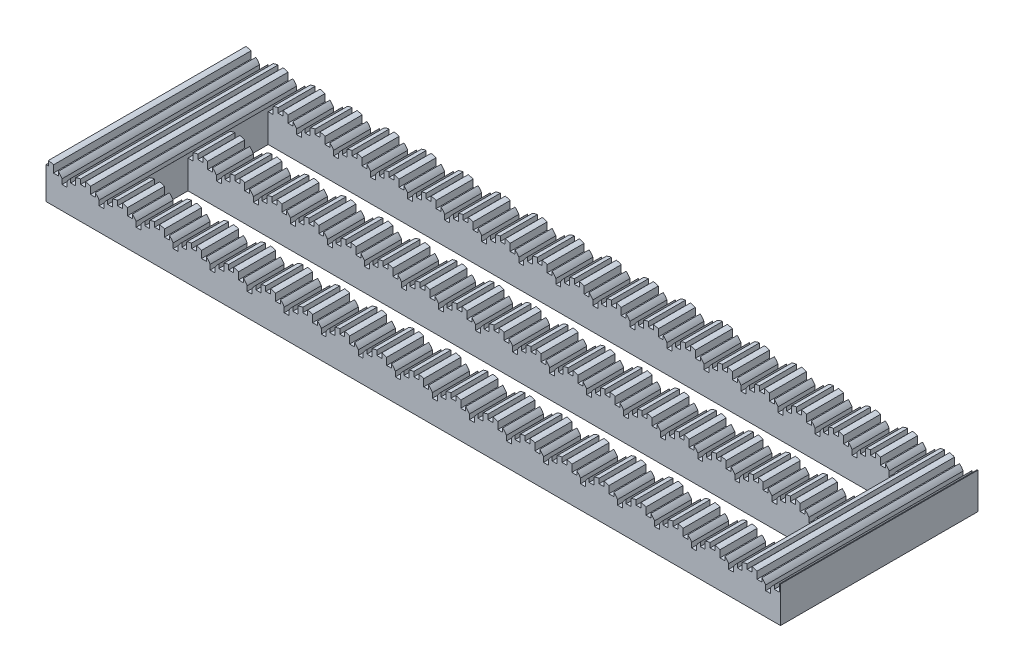
SolidWorks part; units mm, degrees
ref_plane "Front Plane" through (0, 0, 0) normal (0, 0, 1) x (1, 0, 0)
ref_plane "Top Plane" through (0, 0, 0) normal (0, 1, 0) x (1, 0, 0)
ref_plane "Right Plane" through (0, 0, 0) normal (1, 0, 0) x (0, 0, -1)
sketch "Sketch1" plane through (0, 0, 0) normal (0, 1, 0) x (1, 0, 0)
  line L1 (-59.5, -16) -> (59.5, -16)
  line L2 (-59.5, -16) -> (-59.5, 16)
  line L3 (-59.5, 16) -> (59.5, 16)
  line L4 (59.5, -16) -> (59.5, 16)
  line L5 (-59.5, -16) -> (59.5, 16) construction
  line L6 (-59.5, 16) -> (59.5, -16) construction
  line L7 (-49.5, 10) -> (53, 10)
  line L8 (-49.5, 10) -> (-49.5, 3)
  line L9 (-49.5, 3) -> (53, 3)
  line L10 (53, 10) -> (53, 3)
  line L11 (-49.5, -3) -> (53, -3)
  line L12 (-49.5, -3) -> (-49.5, -10)
  line L13 (-49.5, -10) -> (53, -10)
  line L14 (53, -3) -> (53, -10)
  point P0 (0, 0)
  dimension "D1" = 119
  dimension "D2" = 32
  dimension "D3" = 7
  dimension "D4" = 7
  dimension "D5" = 6
  dimension "D6" = 6
  dimension "D7" = 10
  dimension "D8" = 10
  dimension "D9" = 6.5
  dimension "D10" = 6.5
extrude "Boss-Extrude1" add sketch "Sketch1" along normal blind 6
sketch "Sketch2" plane through (0, 0, 16) normal (0, 0, 1) x (1, 0, 0)
  line L0 (-59.5, 6) -> (-59.5, 0) construction
  line L1 (-56.5828, 3.7) -> (-56.4172, 3.7)
  line L3 (-59.5, 6) -> (59.5, 6) construction
  line L4 (-50.5828, 3.7) -> (-50.4172, 3.7)
  line L5 (-44.5828, 3.7) -> (-44.4172, 3.7)
  line L6 (-59.5, 6) -> (-59.5, 9.8546)
  line L7 (-59.5, 9.8546) -> (59.5, 9.8546)
  line L8 (59.5, 9.8546) -> (59.5, 5.8284)
  line L9 (-38.5828, 3.7) -> (-38.4172, 3.7)
  line L10 (-32.5828, 3.7) -> (-32.4172, 3.7)
  line L11 (-26.5828, 3.7) -> (-26.4172, 3.7)
  line L12 (-20.5828, 3.7) -> (-20.4172, 3.7)
  line L13 (-14.5828, 3.7) -> (-14.4172, 3.7)
  line L14 (-8.5828, 3.7) -> (-8.4172, 3.7)
  line L15 (-2.5828, 3.7) -> (-2.4172, 3.7)
  line L16 (3.4172, 3.7) -> (3.5828, 3.7)
  line L17 (9.4172, 3.7) -> (9.5828, 3.7)
  line L18 (15.4172, 3.7) -> (15.5828, 3.7)
  line L19 (21.4172, 3.7) -> (21.5828, 3.7)
  line L20 (27.4172, 3.7) -> (27.5828, 3.7)
  line L21 (33.4172, 3.7) -> (33.5828, 3.7)
  line L22 (39.4172, 3.7) -> (39.5828, 3.7)
  line L23 (45.4172, 3.7) -> (45.5828, 3.7)
  line L24 (51.4172, 3.7) -> (51.5828, 3.7)
  line L25 (57.4172, 3.7) -> (57.5828, 3.7)
  arc A0 (-59.5, 6) -> (-56.5828, 3.7) centre (-59.5, 3) cw
  arc A1 (-50.5828, 3.7) -> (-56.4172, 3.7) centre (-53.5, 3) ccw
  arc A2 (-44.5828, 3.7) -> (-50.4172, 3.7) centre (-47.5, 3) ccw
  arc A3 (-38.5828, 3.7) -> (-44.4172, 3.7) centre (-41.5, 3) ccw
  arc A4 (-32.5828, 3.7) -> (-38.4172, 3.7) centre (-35.5, 3) ccw
  arc A5 (-26.5828, 3.7) -> (-32.4172, 3.7) centre (-29.5, 3) ccw
  arc A6 (-20.5828, 3.7) -> (-26.4172, 3.7) centre (-23.5, 3) ccw
  arc A7 (-14.5828, 3.7) -> (-20.4172, 3.7) centre (-17.5, 3) ccw
  arc A8 (-8.5828, 3.7) -> (-14.4172, 3.7) centre (-11.5, 3) ccw
  arc A9 (-2.5828, 3.7) -> (-8.4172, 3.7) centre (-5.5, 3) ccw
  arc A10 (3.4172, 3.7) -> (-2.4172, 3.7) centre (0.5, 3) ccw
  arc A11 (9.4172, 3.7) -> (3.5828, 3.7) centre (6.5, 3) ccw
  arc A12 (15.4172, 3.7) -> (9.5828, 3.7) centre (12.5, 3) ccw
  arc A13 (21.4172, 3.7) -> (15.5828, 3.7) centre (18.5, 3) ccw
  arc A14 (27.4172, 3.7) -> (21.5828, 3.7) centre (24.5, 3) ccw
  arc A15 (33.4172, 3.7) -> (27.5828, 3.7) centre (30.5, 3) ccw
  arc A16 (39.4172, 3.7) -> (33.5828, 3.7) centre (36.5, 3) ccw
  arc A17 (45.4172, 3.7) -> (39.5828, 3.7) centre (42.5, 3) ccw
  arc A18 (51.4172, 3.7) -> (45.5828, 3.7) centre (48.5, 3) ccw
  arc A19 (57.4172, 3.7) -> (51.5828, 3.7) centre (54.5, 3) ccw
  arc A20 (59.5, 5.8284) -> (57.5828, 3.7) centre (60.5, 3) ccw
  dimension "D1" = 20
extrude "Cut-Extrude1" cut sketch "Sketch2" against normal blind 45
sketch "Sketch3" plane through (0, 0, 16) normal (0, 0, 1) x (1, 0, 0)
  line L0 (-55.5, 4.6) -> (-54.7, 4.6)
  line L1 (-53.9, 5.2) -> (-53.1, 5.2)
  line L2 (-53.9, 5.2) -> (-53.9, 6.8)
  line L3 (-53.9, 6.8) -> (-53.1, 6.8)
  line L4 (-53.1, 5.2) -> (-53.1, 6.8)
  line L5 (-53.9, 5.2) -> (-53.1, 6.8) construction
  line L6 (-53.9, 6.8) -> (-53.1, 5.2) construction
  line L7 (-56.902, 3.6963) -> (-56.102, 3.6963)
  line L8 (-56.902, 3.6963) -> (-56.902, 4.4963)
  line L9 (-56.902, 4.4963) -> (-56.102, 4.4963)
  line L10 (-56.102, 3.6963) -> (-56.102, 4.4963)
  line L11 (-56.902, 3.6963) -> (-56.102, 4.4963) construction
  line L12 (-56.902, 4.4963) -> (-56.102, 3.6963) construction
  line L13 (-55.5, 4.6) -> (-55.5, 6.2067)
  line L14 (-55.5, 6.2067) -> (-54.7, 6.2067)
  line L15 (-54.7, 4.6) -> (-54.7, 6.2067)
  line L16 (-52.3, 4.6) -> (-51.5, 4.6)
  line L17 (-52.3, 4.6) -> (-52.3, 6.2679)
  line L18 (-52.3, 6.2679) -> (-51.5, 6.2679)
  line L19 (-51.5, 4.6) -> (-51.5, 6.2679)
  line L20 (-50.902, 3.6963) -> (-50.902, 4.4963)
  line L21 (-50.902, 3.6963) -> (-50.102, 3.6963)
  line L22 (-50.102, 3.6963) -> (-50.102, 4.4963)
  line L23 (-50.902, 4.4963) -> (-50.102, 4.4963)
  line L24 (-44.902, 3.6963) -> (-44.902, 4.4963)
  line L25 (-44.902, 3.6963) -> (-44.102, 3.6963)
  line L26 (-44.102, 3.6963) -> (-44.102, 4.4963)
  line L27 (-44.902, 4.4963) -> (-44.102, 4.4963)
  line L28 (-38.902, 3.6963) -> (-38.902, 4.4963)
  line L29 (-38.902, 3.6963) -> (-38.102, 3.6963)
  line L30 (-38.102, 3.6963) -> (-38.102, 4.4963)
  line L31 (-38.902, 4.4963) -> (-38.102, 4.4963)
  line L32 (-32.902, 3.6963) -> (-32.902, 4.4963)
  line L33 (-32.902, 3.6963) -> (-32.102, 3.6963)
  line L34 (-32.102, 3.6963) -> (-32.102, 4.4963)
  line L35 (-32.902, 4.4963) -> (-32.102, 4.4963)
  line L36 (-26.902, 3.6963) -> (-26.902, 4.4963)
  line L37 (-26.902, 3.6963) -> (-26.102, 3.6963)
  line L38 (-26.102, 3.6963) -> (-26.102, 4.4963)
  line L39 (-26.902, 4.4963) -> (-26.102, 4.4963)
  line L40 (-20.902, 3.6963) -> (-20.902, 4.4963)
  line L41 (-20.902, 3.6963) -> (-20.102, 3.6963)
  line L42 (-20.102, 3.6963) -> (-20.102, 4.4963)
  line L43 (-20.902, 4.4963) -> (-20.102, 4.4963)
  line L44 (-14.902, 3.6963) -> (-14.902, 4.4963)
  line L45 (-14.902, 3.6963) -> (-14.102, 3.6963)
  line L46 (-14.102, 3.6963) -> (-14.102, 4.4963)
  line L47 (-14.902, 4.4963) -> (-14.102, 4.4963)
  line L48 (-8.902, 3.6963) -> (-8.902, 4.4963)
  line L49 (-8.902, 3.6963) -> (-8.102, 3.6963)
  line L50 (-8.102, 3.6963) -> (-8.102, 4.4963)
  line L51 (-8.902, 4.4963) -> (-8.102, 4.4963)
  line L52 (-2.902, 3.6963) -> (-2.902, 4.4963)
  line L53 (-2.902, 3.6963) -> (-2.102, 3.6963)
  line L54 (-2.102, 3.6963) -> (-2.102, 4.4963)
  line L55 (-2.902, 4.4963) -> (-2.102, 4.4963)
  line L56 (3.098, 3.6963) -> (3.098, 4.4963)
  line L57 (3.098, 3.6963) -> (3.898, 3.6963)
  line L58 (3.898, 3.6963) -> (3.898, 4.4963)
  line L59 (3.098, 4.4963) -> (3.898, 4.4963)
  line L60 (9.098, 3.6963) -> (9.098, 4.4963)
  line L61 (9.098, 3.6963) -> (9.898, 3.6963)
  line L62 (9.898, 3.6963) -> (9.898, 4.4963)
  line L63 (9.098, 4.4963) -> (9.898, 4.4963)
  line L64 (15.098, 3.6963) -> (15.098, 4.4963)
  line L65 (15.098, 3.6963) -> (15.898, 3.6963)
  line L66 (15.898, 3.6963) -> (15.898, 4.4963)
  line L67 (15.098, 4.4963) -> (15.898, 4.4963)
  line L68 (21.098, 3.6963) -> (21.098, 4.4963)
  line L69 (21.098, 3.6963) -> (21.898, 3.6963)
  line L70 (21.898, 3.6963) -> (21.898, 4.4963)
  line L71 (21.098, 4.4963) -> (21.898, 4.4963)
  line L72 (27.098, 3.6963) -> (27.098, 4.4963)
  line L73 (27.098, 3.6963) -> (27.898, 3.6963)
  line L74 (27.898, 3.6963) -> (27.898, 4.4963)
  line L75 (27.098, 4.4963) -> (27.898, 4.4963)
  line L76 (33.098, 3.6963) -> (33.098, 4.4963)
  line L77 (33.098, 3.6963) -> (33.898, 3.6963)
  line L78 (33.898, 3.6963) -> (33.898, 4.4963)
  line L79 (33.098, 4.4963) -> (33.898, 4.4963)
  line L80 (39.098, 3.6963) -> (39.098, 4.4963)
  line L81 (39.098, 3.6963) -> (39.898, 3.6963)
  line L82 (39.898, 3.6963) -> (39.898, 4.4963)
  line L83 (39.098, 4.4963) -> (39.898, 4.4963)
  line L84 (45.098, 3.6963) -> (45.098, 4.4963)
  line L85 (45.098, 3.6963) -> (45.898, 3.6963)
  line L86 (45.898, 3.6963) -> (45.898, 4.4963)
  line L87 (45.098, 4.4963) -> (45.898, 4.4963)
  line L88 (51.098, 3.6963) -> (51.098, 4.4963)
  line L89 (51.098, 3.6963) -> (51.898, 3.6963)
  line L90 (51.898, 3.6963) -> (51.898, 4.4963)
  line L91 (51.098, 4.4963) -> (51.898, 4.4963)
  line L92 (57.098, 3.6963) -> (57.098, 4.4963)
  line L93 (57.098, 3.6963) -> (57.898, 3.6963)
  line L94 (57.898, 3.6963) -> (57.898, 4.4963)
  line L95 (57.098, 4.4963) -> (57.898, 4.4963)
  line L96 (-49.5, 4.6) -> (-48.7, 4.6)
  line L97 (-48.7, 4.6) -> (-48.7, 6.2067)
  line L98 (-49.5, 6.2067) -> (-48.7, 6.2067)
  line L99 (-49.5, 4.6) -> (-49.5, 6.2067)
  line L100 (-47.9, 5.2) -> (-47.9, 6.8)
  line L101 (-47.9, 5.2) -> (-47.1, 5.2)
  line L102 (-47.1, 5.2) -> (-47.1, 6.8)
  line L103 (-47.9, 6.8) -> (-47.1, 6.8)
  line L104 (-46.3, 4.6) -> (-45.5, 4.6)
  line L105 (-45.5, 4.6) -> (-45.5, 6.2679)
  line L106 (-46.3, 6.2679) -> (-45.5, 6.2679)
  line L107 (-46.3, 4.6) -> (-46.3, 6.2679)
  line L108 (-43.5, 4.6) -> (-42.7, 4.6)
  line L109 (-42.7, 4.6) -> (-42.7, 6.2067)
  line L110 (-43.5, 6.2067) -> (-42.7, 6.2067)
  line L111 (-43.5, 4.6) -> (-43.5, 6.2067)
  line L112 (-41.9, 5.2) -> (-41.9, 6.8)
  line L113 (-41.9, 5.2) -> (-41.1, 5.2)
  line L114 (-41.1, 5.2) -> (-41.1, 6.8)
  line L115 (-41.9, 6.8) -> (-41.1, 6.8)
  line L116 (-40.3, 4.6) -> (-39.5, 4.6)
  line L117 (-39.5, 4.6) -> (-39.5, 6.2679)
  line L118 (-40.3, 6.2679) -> (-39.5, 6.2679)
  line L119 (-40.3, 4.6) -> (-40.3, 6.2679)
  line L120 (-37.5, 4.6) -> (-36.7, 4.6)
  line L121 (-36.7, 4.6) -> (-36.7, 6.2067)
  line L122 (-37.5, 6.2067) -> (-36.7, 6.2067)
  line L123 (-37.5, 4.6) -> (-37.5, 6.2067)
  line L124 (-35.9, 5.2) -> (-35.9, 6.8)
  line L125 (-35.9, 5.2) -> (-35.1, 5.2)
  line L126 (-35.1, 5.2) -> (-35.1, 6.8)
  line L127 (-35.9, 6.8) -> (-35.1, 6.8)
  line L128 (-34.3, 4.6) -> (-33.5, 4.6)
  line L129 (-33.5, 4.6) -> (-33.5, 6.2679)
  line L130 (-34.3, 6.2679) -> (-33.5, 6.2679)
  line L131 (-34.3, 4.6) -> (-34.3, 6.2679)
  line L132 (-31.5, 4.6) -> (-30.7, 4.6)
  line L133 (-30.7, 4.6) -> (-30.7, 6.2067)
  line L134 (-31.5, 6.2067) -> (-30.7, 6.2067)
  line L135 (-31.5, 4.6) -> (-31.5, 6.2067)
  line L136 (-29.9, 5.2) -> (-29.9, 6.8)
  line L137 (-29.9, 5.2) -> (-29.1, 5.2)
  line L138 (-29.1, 5.2) -> (-29.1, 6.8)
  line L139 (-29.9, 6.8) -> (-29.1, 6.8)
  line L140 (-28.3, 4.6) -> (-27.5, 4.6)
  line L141 (-27.5, 4.6) -> (-27.5, 6.2679)
  line L142 (-28.3, 6.2679) -> (-27.5, 6.2679)
  line L143 (-28.3, 4.6) -> (-28.3, 6.2679)
  line L144 (-25.5, 4.6) -> (-24.7, 4.6)
  line L145 (-24.7, 4.6) -> (-24.7, 6.2067)
  line L146 (-25.5, 6.2067) -> (-24.7, 6.2067)
  line L147 (-25.5, 4.6) -> (-25.5, 6.2067)
  line L148 (-23.9, 5.2) -> (-23.9, 6.8)
  line L149 (-23.9, 5.2) -> (-23.1, 5.2)
  line L150 (-23.1, 5.2) -> (-23.1, 6.8)
  line L151 (-23.9, 6.8) -> (-23.1, 6.8)
  line L152 (-22.3, 4.6) -> (-21.5, 4.6)
  line L153 (-21.5, 4.6) -> (-21.5, 6.2679)
  line L154 (-22.3, 6.2679) -> (-21.5, 6.2679)
  line L155 (-22.3, 4.6) -> (-22.3, 6.2679)
  line L156 (-19.5, 4.6) -> (-18.7, 4.6)
  line L157 (-18.7, 4.6) -> (-18.7, 6.2067)
  line L158 (-19.5, 6.2067) -> (-18.7, 6.2067)
  line L159 (-19.5, 4.6) -> (-19.5, 6.2067)
  line L160 (-17.9, 5.2) -> (-17.9, 6.8)
  line L161 (-17.9, 5.2) -> (-17.1, 5.2)
  line L162 (-17.1, 5.2) -> (-17.1, 6.8)
  line L163 (-17.9, 6.8) -> (-17.1, 6.8)
  line L164 (-16.3, 4.6) -> (-15.5, 4.6)
  line L165 (-15.5, 4.6) -> (-15.5, 6.2679)
  line L166 (-16.3, 6.2679) -> (-15.5, 6.2679)
  line L167 (-16.3, 4.6) -> (-16.3, 6.2679)
  line L168 (-13.5, 4.6) -> (-12.7, 4.6)
  line L169 (-12.7, 4.6) -> (-12.7, 6.2067)
  line L170 (-13.5, 6.2067) -> (-12.7, 6.2067)
  line L171 (-13.5, 4.6) -> (-13.5, 6.2067)
  line L172 (-11.9, 5.2) -> (-11.9, 6.8)
  line L173 (-11.9, 5.2) -> (-11.1, 5.2)
  line L174 (-11.1, 5.2) -> (-11.1, 6.8)
  line L175 (-11.9, 6.8) -> (-11.1, 6.8)
  line L176 (-10.3, 4.6) -> (-9.5, 4.6)
  line L177 (-9.5, 4.6) -> (-9.5, 6.2679)
  line L178 (-10.3, 6.2679) -> (-9.5, 6.2679)
  line L179 (-10.3, 4.6) -> (-10.3, 6.2679)
  line L180 (-7.5, 4.6) -> (-6.7, 4.6)
  line L181 (-6.7, 4.6) -> (-6.7, 6.2067)
  line L182 (-7.5, 6.2067) -> (-6.7, 6.2067)
  line L183 (-7.5, 4.6) -> (-7.5, 6.2067)
  line L184 (-5.9, 5.2) -> (-5.9, 6.8)
  line L185 (-5.9, 5.2) -> (-5.1, 5.2)
  line L186 (-5.1, 5.2) -> (-5.1, 6.8)
  line L187 (-5.9, 6.8) -> (-5.1, 6.8)
  line L188 (-4.3, 4.6) -> (-3.5, 4.6)
  line L189 (-3.5, 4.6) -> (-3.5, 6.2679)
  line L190 (-4.3, 6.2679) -> (-3.5, 6.2679)
  line L191 (-4.3, 4.6) -> (-4.3, 6.2679)
  line L192 (-1.5, 4.6) -> (-0.7, 4.6)
  line L193 (-0.7, 4.6) -> (-0.7, 6.2067)
  line L194 (-1.5, 6.2067) -> (-0.7, 6.2067)
  line L195 (-1.5, 4.6) -> (-1.5, 6.2067)
  line L196 (0.1, 5.2) -> (0.1, 6.8)
  line L197 (0.1, 5.2) -> (0.9, 5.2)
  line L198 (0.9, 5.2) -> (0.9, 6.8)
  line L199 (0.1, 6.8) -> (0.9, 6.8)
  line L200 (1.7, 4.6) -> (2.5, 4.6)
  line L201 (2.5, 4.6) -> (2.5, 6.2679)
  line L202 (1.7, 6.2679) -> (2.5, 6.2679)
  line L203 (1.7, 4.6) -> (1.7, 6.2679)
  line L204 (4.5, 4.6) -> (5.3, 4.6)
  line L205 (5.3, 4.6) -> (5.3, 6.2067)
  line L206 (4.5, 6.2067) -> (5.3, 6.2067)
  line L207 (4.5, 4.6) -> (4.5, 6.2067)
  line L208 (6.1, 5.2) -> (6.1, 6.8)
  line L209 (6.1, 5.2) -> (6.9, 5.2)
  line L210 (6.9, 5.2) -> (6.9, 6.8)
  line L211 (6.1, 6.8) -> (6.9, 6.8)
  line L212 (7.7, 4.6) -> (8.5, 4.6)
  line L213 (8.5, 4.6) -> (8.5, 6.2679)
  line L214 (7.7, 6.2679) -> (8.5, 6.2679)
  line L215 (7.7, 4.6) -> (7.7, 6.2679)
  line L216 (10.5, 4.6) -> (11.3, 4.6)
  line L217 (11.3, 4.6) -> (11.3, 6.2067)
  line L218 (10.5, 6.2067) -> (11.3, 6.2067)
  line L219 (10.5, 4.6) -> (10.5, 6.2067)
  line L220 (12.1, 5.2) -> (12.1, 6.8)
  line L221 (12.1, 5.2) -> (12.9, 5.2)
  line L222 (12.9, 5.2) -> (12.9, 6.8)
  line L223 (12.1, 6.8) -> (12.9, 6.8)
  line L224 (13.7, 4.6) -> (14.5, 4.6)
  line L225 (14.5, 4.6) -> (14.5, 6.2679)
  line L226 (13.7, 6.2679) -> (14.5, 6.2679)
  line L227 (13.7, 4.6) -> (13.7, 6.2679)
  line L228 (16.5, 4.6) -> (17.3, 4.6)
  line L229 (17.3, 4.6) -> (17.3, 6.2067)
  line L230 (16.5, 6.2067) -> (17.3, 6.2067)
  line L231 (16.5, 4.6) -> (16.5, 6.2067)
  line L232 (18.1, 5.2) -> (18.1, 6.8)
  line L233 (18.1, 5.2) -> (18.9, 5.2)
  line L234 (18.9, 5.2) -> (18.9, 6.8)
  line L235 (18.1, 6.8) -> (18.9, 6.8)
  line L236 (19.7, 4.6) -> (20.5, 4.6)
  line L237 (20.5, 4.6) -> (20.5, 6.2679)
  line L238 (19.7, 6.2679) -> (20.5, 6.2679)
  line L239 (19.7, 4.6) -> (19.7, 6.2679)
  line L240 (22.5, 4.6) -> (23.3, 4.6)
  line L241 (23.3, 4.6) -> (23.3, 6.2067)
  line L242 (22.5, 6.2067) -> (23.3, 6.2067)
  line L243 (22.5, 4.6) -> (22.5, 6.2067)
  line L244 (24.1, 5.2) -> (24.1, 6.8)
  line L245 (24.1, 5.2) -> (24.9, 5.2)
  line L246 (24.9, 5.2) -> (24.9, 6.8)
  line L247 (24.1, 6.8) -> (24.9, 6.8)
  line L248 (25.7, 4.6) -> (26.5, 4.6)
  line L249 (26.5, 4.6) -> (26.5, 6.2679)
  line L250 (25.7, 6.2679) -> (26.5, 6.2679)
  line L251 (25.7, 4.6) -> (25.7, 6.2679)
  line L252 (28.5, 4.6) -> (29.3, 4.6)
  line L253 (29.3, 4.6) -> (29.3, 6.2067)
  line L254 (28.5, 6.2067) -> (29.3, 6.2067)
  line L255 (28.5, 4.6) -> (28.5, 6.2067)
  line L256 (30.1, 5.2) -> (30.1, 6.8)
  line L257 (30.1, 5.2) -> (30.9, 5.2)
  line L258 (30.9, 5.2) -> (30.9, 6.8)
  line L259 (30.1, 6.8) -> (30.9, 6.8)
  line L260 (31.7, 4.6) -> (32.5, 4.6)
  line L261 (32.5, 4.6) -> (32.5, 6.2679)
  line L262 (31.7, 6.2679) -> (32.5, 6.2679)
  line L263 (31.7, 4.6) -> (31.7, 6.2679)
  line L264 (34.5, 4.6) -> (35.3, 4.6)
  line L265 (35.3, 4.6) -> (35.3, 6.2067)
  line L266 (34.5, 6.2067) -> (35.3, 6.2067)
  line L267 (34.5, 4.6) -> (34.5, 6.2067)
  line L268 (36.1, 5.2) -> (36.1, 6.8)
  line L269 (36.1, 5.2) -> (36.9, 5.2)
  line L270 (36.9, 5.2) -> (36.9, 6.8)
  line L271 (36.1, 6.8) -> (36.9, 6.8)
  line L272 (37.7, 4.6) -> (38.5, 4.6)
  line L273 (38.5, 4.6) -> (38.5, 6.2679)
  line L274 (37.7, 6.2679) -> (38.5, 6.2679)
  line L275 (37.7, 4.6) -> (37.7, 6.2679)
  line L276 (40.5, 4.6) -> (41.3, 4.6)
  line L277 (41.3, 4.6) -> (41.3, 6.2067)
  line L278 (40.5, 6.2067) -> (41.3, 6.2067)
  line L279 (40.5, 4.6) -> (40.5, 6.2067)
  line L280 (42.1, 5.2) -> (42.1, 6.8)
  line L281 (42.1, 5.2) -> (42.9, 5.2)
  line L282 (42.9, 5.2) -> (42.9, 6.8)
  line L283 (42.1, 6.8) -> (42.9, 6.8)
  line L284 (43.7, 4.6) -> (44.5, 4.6)
  line L285 (44.5, 4.6) -> (44.5, 6.2679)
  line L286 (43.7, 6.2679) -> (44.5, 6.2679)
  line L287 (43.7, 4.6) -> (43.7, 6.2679)
  line L288 (46.5, 4.6) -> (47.3, 4.6)
  line L289 (47.3, 4.6) -> (47.3, 6.2067)
  line L290 (46.5, 6.2067) -> (47.3, 6.2067)
  line L291 (46.5, 4.6) -> (46.5, 6.2067)
  line L292 (48.1, 5.2) -> (48.1, 6.8)
  line L293 (48.1, 5.2) -> (48.9, 5.2)
  line L294 (48.9, 5.2) -> (48.9, 6.8)
  line L295 (48.1, 6.8) -> (48.9, 6.8)
  line L296 (49.7, 4.6) -> (50.5, 4.6)
  line L297 (50.5, 4.6) -> (50.5, 6.2679)
  line L298 (49.7, 6.2679) -> (50.5, 6.2679)
  line L299 (49.7, 4.6) -> (49.7, 6.2679)
  line L300 (52.5, 4.6) -> (53.3, 4.6)
  line L301 (53.3, 4.6) -> (53.3, 6.2067)
  line L302 (52.5, 6.2067) -> (53.3, 6.2067)
  line L303 (52.5, 4.6) -> (52.5, 6.2067)
  line L304 (54.1, 5.2) -> (54.1, 6.8)
  line L305 (54.1, 5.2) -> (54.9, 5.2)
  line L306 (54.9, 5.2) -> (54.9, 6.8)
  line L307 (54.1, 6.8) -> (54.9, 6.8)
  line L308 (55.7, 4.6) -> (56.5, 4.6)
  line L309 (56.5, 4.6) -> (56.5, 6.2679)
  line L310 (55.7, 6.2679) -> (56.5, 6.2679)
  line L311 (55.7, 4.6) -> (55.7, 6.2679)
  line L312 (58.5, 4.6) -> (59.3, 4.6)
  line L313 (59.3, 4.6) -> (59.3, 6.2067)
  line L314 (58.5, 6.2067) -> (59.3, 6.2067)
  line L315 (58.5, 4.6) -> (58.5, 6.2067)
  line L316 (60.1, 5.2) -> (60.1, 6.8)
  line L317 (60.1, 5.2) -> (60.9, 5.2)
  line L318 (60.9, 5.2) -> (60.9, 6.8)
  line L319 (60.1, 6.8) -> (60.9, 6.8)
  line L320 (61.7, 4.6) -> (62.5, 4.6)
  line L321 (62.5, 4.6) -> (62.5, 6.2679)
  line L322 (61.7, 6.2679) -> (62.5, 6.2679)
  line L323 (61.7, 4.6) -> (61.7, 6.2679)
  line L324 (64.5, 4.6) -> (65.3, 4.6)
  line L325 (65.3, 4.6) -> (65.3, 6.2067)
  line L326 (64.5, 6.2067) -> (65.3, 6.2067)
  line L327 (64.5, 4.6) -> (64.5, 6.2067)
  line L328 (66.1, 5.2) -> (66.1, 6.8)
  line L329 (66.1, 5.2) -> (66.9, 5.2)
  line L330 (66.9, 5.2) -> (66.9, 6.8)
  line L331 (66.1, 6.8) -> (66.9, 6.8)
  line L332 (67.7, 4.6) -> (68.5, 4.6)
  line L333 (68.5, 4.6) -> (68.5, 6.2679)
  line L334 (67.7, 6.2679) -> (68.5, 6.2679)
  line L335 (67.7, 4.6) -> (67.7, 6.2679)
  line L336 (-59.9, 5.2) -> (-59.9, 6.8)
  line L337 (-59.9, 5.2) -> (-59.1, 5.2)
  line L338 (-59.1, 5.2) -> (-59.1, 6.8)
  line L339 (-59.9, 6.8) -> (-59.1, 6.8)
  line L340 (-58.3, 4.6) -> (-57.5, 4.6)
  line L341 (-57.5, 4.6) -> (-57.5, 6.2679)
  line L342 (-58.3, 6.2679) -> (-57.5, 6.2679)
  line L343 (-58.3, 4.6) -> (-58.3, 6.2679)
  line L344 (-61.5, 4.6) -> (-60.7, 4.6)
  line L345 (-60.7, 4.6) -> (-60.7, 6.2067)
  line L346 (-61.5, 6.2067) -> (-60.7, 6.2067)
  line L347 (-61.5, 4.6) -> (-61.5, 6.2067)
  arc A0 (-50.5828, 3.7) -> (-56.4172, 3.7) centre (-53.5, 3) ccw construction
  point P0 (-53.5, 6)
  point P8 (-56.502, 3.6963)
  dimension "D1" = 0.8
  dimension "D2" = 1.6
  dimension "D3" = 0.8
  dimension "D4" = 0.8
  dimension "D5" = 0.8
  dimension "D6" = 0.8
  dimension "D7" = 0.9037
  dimension "D8" = 0.8
  dimension "D10" = 20
  dimension "D11" = 21
  dimension "D12" = 2
extrude "Cut-Extrude2" cut sketch "Sketch3" against normal through all
